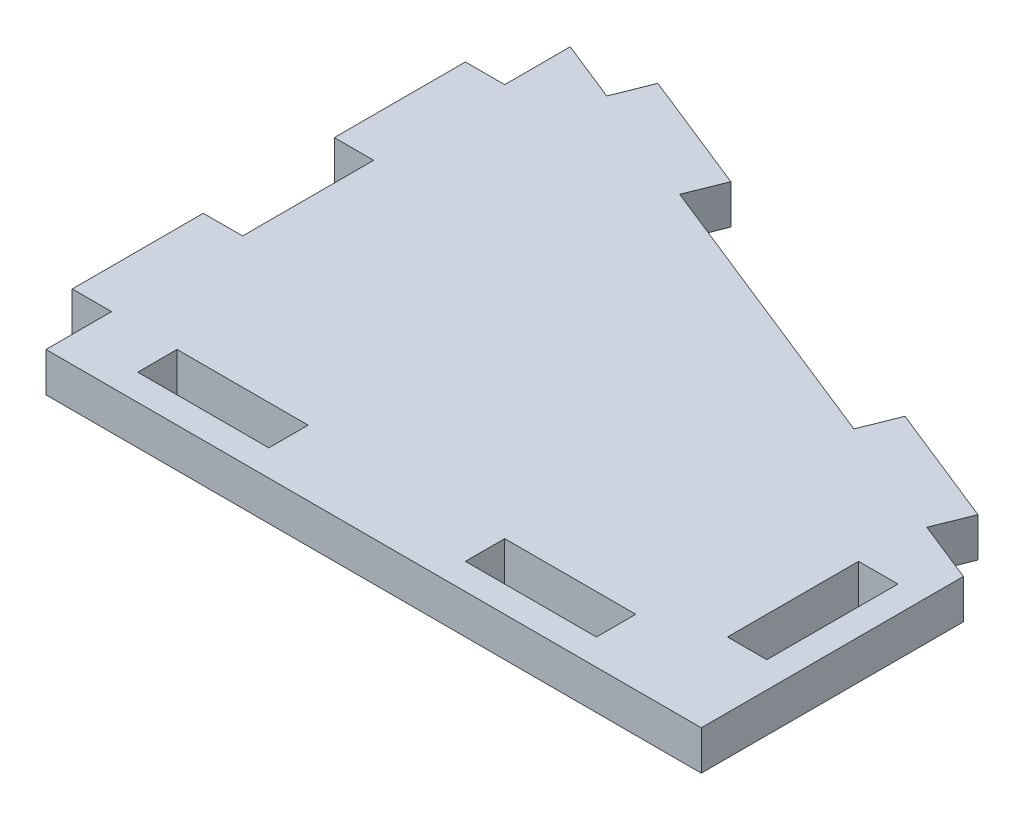
SolidWorks part; units mm, degrees
material "ABS"
ref_plane "Front Plane" through (0, 0, 0) normal (0, 0, 1) x (1, 0, 0)
ref_plane "Top Plane" through (0, 0, 0) normal (0, 1, 0) x (1, 0, 0)
ref_plane "Right Plane" through (0, 0, 0) normal (1, 0, 0) x (0, 0, -1)
sketch "Sketch1" plane through (0, 0, 0) normal (0, 1, 0) x (1, 0, 0)
  line L0 (0, 0) -> (0, 5)
  line L1 (0, 40) -> (4.6424, 38.143)
  line L2 (50, 20) -> (50, 0)
  line L3 (50, 0) -> (0, 0)
  line L4 (0, 35) -> (0, 40)
  line L13 (0, 25) -> (-3, 25)
  line L15 (0, 35) -> (-3, 35)
  line L16 (-3, 25) -> (-3, 35)
  line L17 (0, 15) -> (-3, 15)
  line L19 (0, 5) -> (-3, 5)
  line L20 (-3, 15) -> (-3, 5)
  line L21 (5, 5) -> (15, 5)
  line L22 (5, 5) -> (5, 2)
  line L23 (5, 2) -> (15, 2)
  line L24 (15, 5) -> (15, 2)
  line L25 (30, 5) -> (40, 5)
  line L26 (30, 5) -> (30, 2)
  line L27 (30, 2) -> (40, 2)
  line L28 (40, 5) -> (40, 2)
  line L29 (45, 17) -> (48, 17)
  line L30 (45, 17) -> (45, 7)
  line L31 (45, 7) -> (48, 7)
  line L32 (48, 17) -> (48, 7)
  line L33 (0, 15) -> (0, 25)
  line L34 (4.6424, 38.143) -> (5.7566, 40.9285)
  line L35 (5.7566, 40.9285) -> (15.0413, 37.2146)
  line L36 (15.0413, 37.2146) -> (13.9272, 34.4291)
  line L37 (36.0728, 25.5709) -> (37.187, 28.3563)
  line L38 (37.187, 28.3563) -> (46.4718, 24.6424)
  line L39 (46.4718, 24.6424) -> (45.3576, 21.857)
  line L40 (13.9272, 34.4291) -> (36.0728, 25.5709)
  line L41 (45.3576, 21.857) -> (50, 20)
  point P31 (0, 0)
  dimension "D1" = 50
  dimension "D2" = 20
  dimension "D3" = 40
  dimension "D4" = 10
  dimension "D5" = 10
  dimension "D6" = 3
  dimension "D7" = 3
  dimension "D8" = 2
  dimension "D9" = 2
  dimension "D10" = 10
  dimension "D11" = 3
  dimension "D12" = 2
  dimension "D13" = 7
  dimension "D14" = 10
  dimension "D15" = 3
  dimension "D16" = 10
  dimension "D17" = 3
  dimension "D18" = 5
  dimension "D19" = 5
  dimension "D20" = 10
  dimension "D21" = 3
  dimension "D22" = 3
  dimension "D23" = 10
  dimension "D24" = 5
  dimension "D25" = 5
  dimension "D26" = 10
  dimension "D27" = 15
extrude "Boss-Extrude1" add sketch "Sketch1" along normal blind 3
